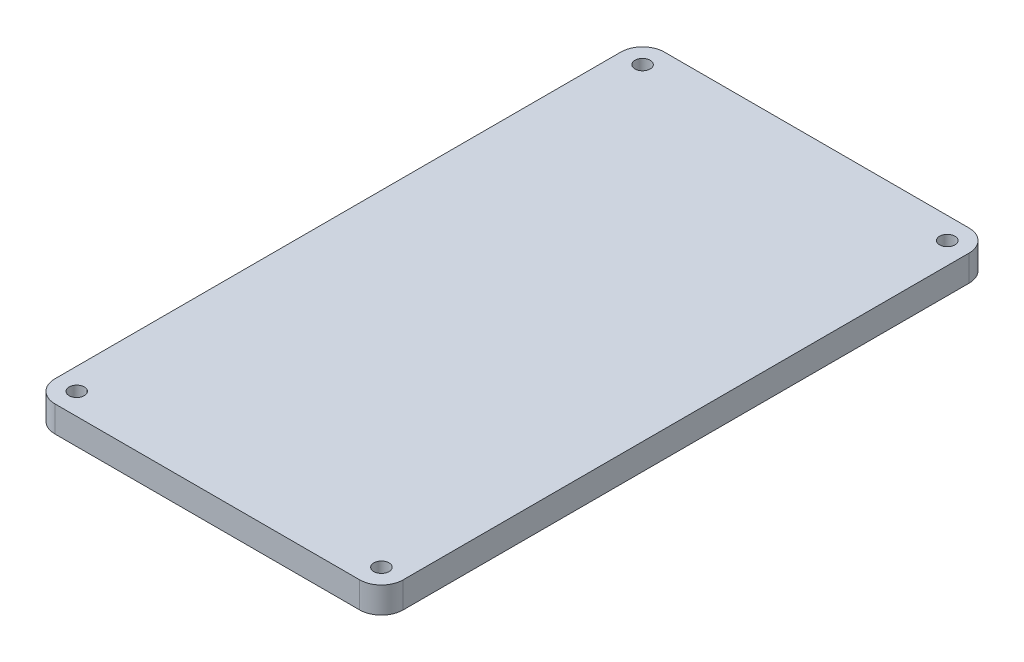
SolidWorks part; units mm, degrees
ref_plane "Front Plane" through (0, 0, 0) normal (0, 0, 1) x (1, 0, 0)
ref_plane "Top Plane" through (0, 0, 0) normal (0, 1, 0) x (1, 0, 0)
ref_plane "Right Plane" through (0, 0, 0) normal (1, 0, 0) x (0, 0, -1)
sketch "Sketch1" plane through (0, 0, 0) normal (0, 1, 0) x (1, 0, 0)
  line L1 (-40, 70) -> (40, 70)
  line L2 (-40, 70) -> (-40, -70)
  line L3 (-40, -70) -> (40, -70)
  line L4 (40, 70) -> (40, -70)
  line L5 (-40, 70) -> (40, -70) construction
  line L6 (-40, -70) -> (40, 70) construction
  point P0 (0, 0)
  dimension "D1" = 140
  dimension "D2" = 80
extrude "Boss-Extrude1" add sketch "Sketch1" along normal blind 6
sketch "Sketch2" plane through (0, 6, 0) normal (0, 1, 0) x (1, 0, 0)
  line L0 (-40, 70) -> (-40, -70) construction
  line L1 (40, 70) -> (-40, 70) construction
  line L2 (-40, -70) -> (40, -70) construction
  line L3 (40, -70) -> (40, 70) construction
  circle A0 centre (-35, 65) radius 1.75
  circle A1 centre (35, 65) radius 1.75
  circle A2 centre (-35, -65) radius 1.75
  circle A3 centre (35, -65) radius 1.75
  point P12 (0, 0)
  point P13 (0, 0)
  point P14 (0, 0)
  point P15 (0, 0)
  dimension "D1" = 3.5
  dimension "D2" = 5
  dimension "D3" = 5
  dimension "D4" = 5
  dimension "D5" = 5
extrude "Cut-Extrude1" cut sketch "Sketch2" against normal through all
fillet "Fillet1" radius 5 4 edges at (-40, 3, -70) (40, 3, -70) (-40, 3, 70) (40, 3, 70)
equation "\"D4@Sketch2\"=\"D2@Sketch2\""
equation "\"D3@Sketch2\"=\"D2@Sketch2\""
equation "\"D5@Sketch2\"=\"D2@Sketch2\""
